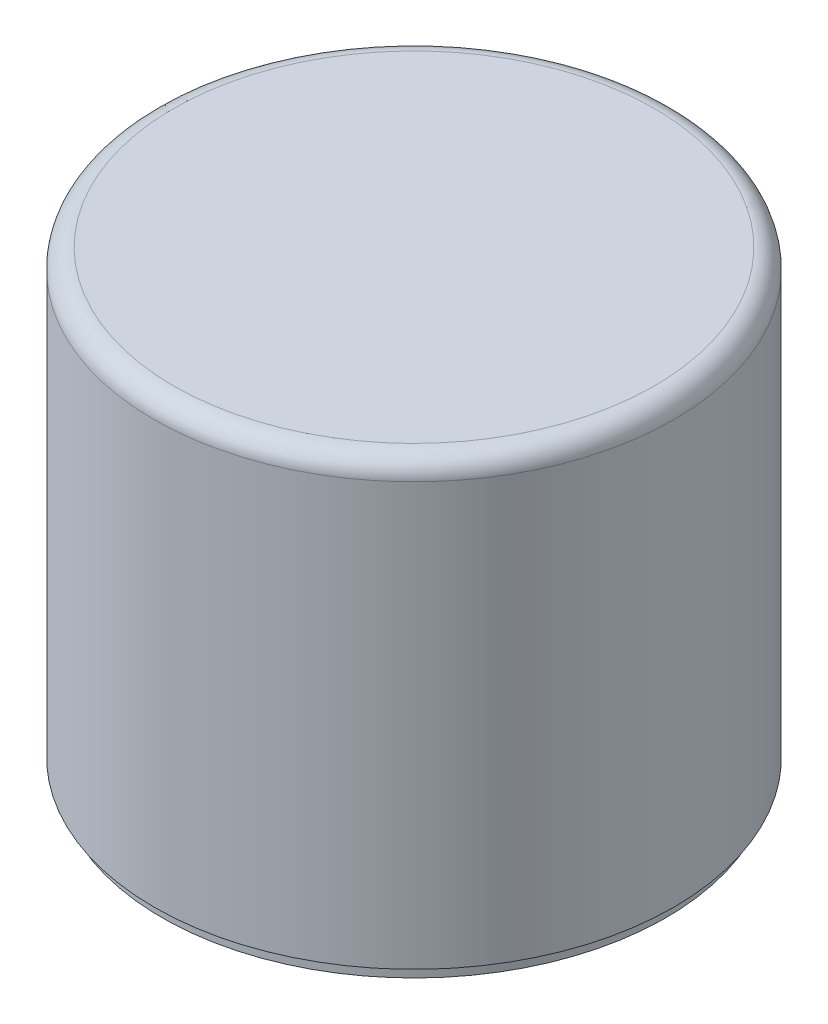
SolidWorks part; units mm, degrees
ref_plane "Front Plane" through (0, 0, 0) normal (0, 0, 1) x (1, 0, 0)
ref_plane "Top Plane" through (0, 0, 0) normal (0, 1, 0) x (1, 0, 0)
ref_plane "Right Plane" through (0, 0, 0) normal (1, 0, 0) x (0, 0, -1)
sketch "Sketch1" plane through (0, 0, 0) normal (0, 1, 0) x (1, 0, 0)
  circle A0 centre (0, 0) radius 40
extrude "Boss-Extrude1" add sketch "Sketch1" along normal blind 70
shell "Shell1" thickness 2
sketch "Sketch2" plane through (0, 0, 0) normal (0, -1, 0) x (1, 0, 0)
  circle A0 centre (0, 0) radius 38.8
  circle A1 centre (0, 0) radius 40
extrude "Cut-Extrude1" cut sketch "Sketch2" against normal blind 2
fillet "Fillet1" radius 3 1 edges at (0, 70, 40)
